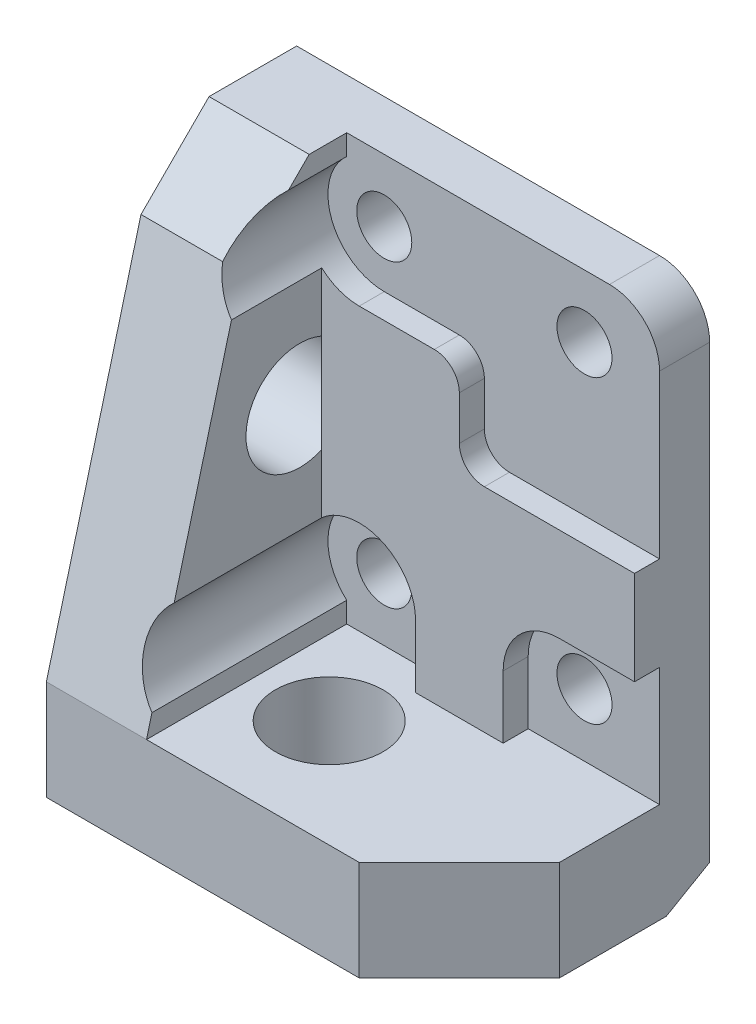
SolidWorks part; units mm, degrees
ref_plane "前视基准面" through (0, 0, 0) normal (0, 0, 1) x (1, 0, 0)
ref_plane "上视基准面" through (0, 0, 0) normal (0, 1, 0) x (1, 0, 0)
ref_plane "右视基准面" through (0, 0, 0) normal (1, 0, 0) x (0, 0, -1)
sketch "草图1" plane through (0, 0, 0) normal (0, 0, 1) x (1, 0, 0)
  line L0 (0, 0) -> (8, 0) construction
  line L1 (8, 0) -> (8, 12) construction
  line L2 (8, 12) -> (0, 12) construction
  line L3 (0, 12) -> (0, 0) construction
  line L4 (0, 6) -> (8, 6) construction
  line L5 (-7.5, 14.5) -> (15.5, 14.5)
  line L6 (-7.5, 14.5) -> (-7.5, -2.5)
  line L7 (-7.5, -2.5) -> (15.5, -2.5)
  line L8 (15.5, 14.5) -> (15.5, -2.5)
  line L9 (4, 12) -> (4, 14.5) construction
  circle A0 centre (0, 0) radius 1.1
  circle A1 centre (8, 0) radius 1.1
  circle A2 centre (0, 12) radius 1.1
  circle A3 centre (8, 12) radius 1.1
  dimension "D1" = 2.2
  dimension "D2" = 12
  dimension "D3" = 8
  dimension "D4" = 17
  dimension "D5" = 23
extrude "凸台-拉伸1" add sketch "草图1" along normal blind 3
sketch "草图2" plane through (-7.5, 0, 0) normal (-1, 0, 0) x (0, 0, 1)
  line L0 (5.5, 14.5) -> (10, -2.5)
  line L1 (0, 14.5) -> (5.5, 14.5)
  line L2 (0, 14.5) -> (0, -2.5)
  line L3 (0, -2.5) -> (5.5, -2.5)
  line L4 (5.5, 14.5) -> (5.5, -2.5) construction
  line L5 (10, -2.5) -> (5.5, -2.5)
  dimension "D1" = 5.5
  dimension "D2" = 4.5
extrude "凸台-拉伸2" add sketch "草图2" against normal blind 6
sketch "草图3" plane through (0, 0, 3) normal (0, 0, 1) x (1, 0, 0)
  circle A0 centre (0, 12) radius 2.25
  circle A1 centre (8, 12) radius 2.25
  circle A2 centre (0, 12) radius 1.1 construction
  circle A3 centre (0, 0) radius 2.25
  circle A4 centre (8, 0) radius 2.25
  dimension "D1" = 4.5
extrude "切除-拉伸1" cut sketch "草图3" against normal blind 1 and the other way through all
sketch "草图4" plane through (0, 0, 3) normal (0, 0, 1) x (1, 0, 0)
  line L0 (15.5, 14.5) -> (-1.5, 14.5) construction
  line L1 (11, 14.5) -> (15.5, 14.5)
  line L2 (11, 14.5) -> (11, -2.5)
  line L3 (11, -2.5) -> (15.5, -2.5)
  line L4 (15.5, 14.5) -> (15.5, -2.5)
  dimension "D1" = 4.5
extrude "切除-拉伸2" cut sketch "草图4" against normal up to next
sketch "草图5" plane through (-7.5, 0, 0) normal (-1, 0, 0) x (0, 0, 1)
  line L4 (0, 14.5) -> (0, -2.5)
  line L5 (0, -2.5) -> (10, -2.5)
  line L6 (10, -2.5) -> (5.5, 14.5)
  line L7 (5.5, 14.5) -> (0, 14.5)
  line L8 (0, 14.5) -> (0, -2.5)
  line L9 (0, -2.5) -> (10, -2.5)
  line L11 (5.5, 14.5) -> (0, 14.5)
  line L12 (10, -2.5) -> (5.5, 14.5)
  dimension "D1" = 0
extrude "切除-拉伸3" cut sketch "草图5" against normal blind 2
sketch "草图6" plane through (-5.5, 0, 0) normal (-1, 0, 0) x (0, 0, 1)
  line L0 (2.75, 14.5) -> (5, -2.5) construction
  line L1 (5.5, 14.5) -> (0, 14.5) construction
  line L2 (0, -2.5) -> (10, -2.5) construction
  circle A1 centre (3.875, 6) radius 2.15
  dimension "D2" = 4.3
extrude "切除-拉伸4" cut sketch "草图6" against normal blind 4
sketch "草图7" plane through (0, -2.5, 0) normal (0, -1, 0) x (1, 0, 0)
  line L1 (-5.5, 10) -> (11, 10)
  line L2 (-5.5, 10) -> (-5.5, 0)
  line L3 (-5.5, 0) -> (11, 0)
  line L4 (11, 10) -> (11, 0)
extrude "凸台-拉伸3" add sketch "草图7" along normal blind 4
sketch "草图8" plane through (0, -6.5, 0) normal (0, -1, 0) x (1, 0, 0)
  line L0 (-5.5, 5.7) -> (11, 5.7) construction
  line L1 (-5.5, 10) -> (-5.5, 0) construction
  line L2 (11, 0) -> (11, 10) construction
  line L3 (-5.5, 0) -> (11, 0) construction
  circle A0 centre (1.5, 5.7) radius 2.15
  dimension "D2" = 4.3
  dimension "D3" = 7
  dimension "D1" = 5.7
extrude "切除-拉伸5" cut sketch "草图8" against normal up to surface (4 mm away) up to face at (4.75, -2.5, 6.5)
chamfer "倒角1" distance 1 angle 60 1 edges at (2.75, -6.5, 0)
chamfer "倒角2" distance 4 angle 45 1 edges at (11, -4.5, 10)
sketch "草图9" plane through (0, 0, 3) normal (0, 0, 1) x (1, 0, 0)
  line L0 (-1.5, 13.6771) -> (-1.5, 14.5)
  line L1 (-1.5, 14.5) -> (2.25, 14.5)
  line L2 (11, 14.5) -> (-1.5, 14.5) construction
  line L3 (2.25, 14.5) -> (2.25, 12)
  line L4 (5.75, 12) -> (5.75, 14.5)
  line L5 (5.75, 14.5) -> (11, 14.5)
  line L6 (11, 14.5) -> (11, 9.75)
  line L7 (11, 14.5) -> (11, -2.5) construction
  line L8 (11, 9.75) -> (8, 9.75)
  line L9 (2.25, 0) -> (2.25, -2.5)
  line L10 (7, -2.5) -> (-1.5, -2.5) construction
  line L11 (2.25, -2.5) -> (-1.5, -2.5)
  line L12 (-1.5, -2.5) -> (-1.5, -1.6771)
  line L13 (5.75, 0) -> (5.75, -2.5)
  line L14 (-1.5, -2.5) -> (11, -2.5) construction
  line L15 (5.75, -2.5) -> (11, -2.5)
  line L16 (11, -2.5) -> (11, 2.25)
  line L17 (11, 2.25) -> (8, 2.25)
  arc A0 (-1.5, 10.3229) -> (-1.5, 13.6771) centre (0, 12) ccw construction
  circle A1 centre (8, 12) radius 2.25 construction
  circle A2 centre (8, 12) radius 2.25 construction
  arc A3 (2.25, 12) -> (-1.5, 13.6771) centre (0, 12) ccw
  arc A4 (8, 9.75) -> (5.75, 12) centre (8, 12) ccw
  arc A5 (-1.5, -1.6771) -> (-1.5, 1.6771) centre (0, 0) ccw construction
  circle A6 centre (8, 0) radius 2.25 construction
  circle A7 centre (8, 0) radius 2.25 construction
  arc A8 (5.75, 0) -> (8, 2.25) centre (8, 0) ccw
  arc A9 (-1.5, -1.6771) -> (2.25, 0) centre (0, 0) ccw
extrude "切除-拉伸6" cut sketch "草图9" against normal up to surface (1 mm away) up to face at (1.1, 12, 2)
fillet "圆角1" radius 2 1 edges at (11, 14.5, 1)
sketch "草图10" plane through (0, 0, 2) normal (0, 0, 1) x (1, 0, 0)
  line L0 (5.75, 14.5) -> (2.25, 14.5) construction
  line L1 (4, 14.5) -> (11, 14.5)
  line L2 (4, 9.75) -> (4, 6)
  line L3 (4, 6) -> (11, 6)
  line L4 (11, 14.5) -> (11, 6)
  line L5 (11, 9.75) -> (11, 2.25) construction
  line L6 (0, 9.75) -> (4, 9.75)
  line L7 (2.25, 14.5) -> (2.25, 12) construction
  line L8 (2.25, 14.5) -> (4, 14.5)
  line L9 (2.25, 14.5) -> (2.25, 12)
  arc A0 (-1.5, 13.6771) -> (2.25, 12) centre (0, 12) ccw construction
  arc A1 (-1.5, 10.3229) -> (2.25, 12) centre (0, 12) ccw construction
  arc A2 (0, 9.75) -> (2.25, 12) centre (0, 12) ccw
extrude "切除-拉伸7" cut sketch "草图10" along normal up to next
fillet "圆角2" radius 1 2 edges at (4, 6, 2.5) (4, 9.75, 2.5)
chamfer "倒角3" distance 2 angle 45 1 edges at (-3.5, 14.5, 5.5)
